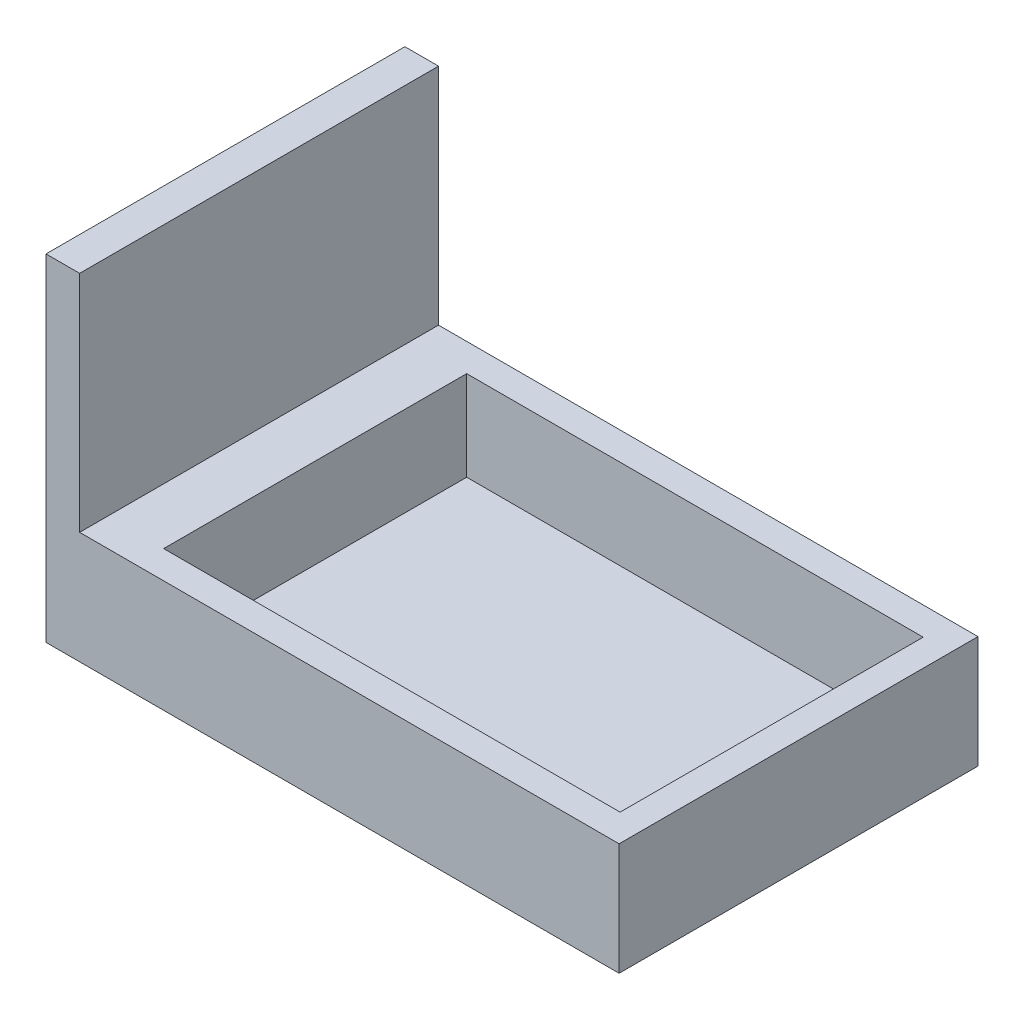
SolidWorks part; units mm, degrees
ref_plane "Front Plane" through (0, 0, 0) normal (0, 0, 1) x (1, 0, 0)
ref_plane "Top Plane" through (0, 0, 0) normal (0, 1, 0) x (1, 0, 0)
ref_plane "Right Plane" through (0, 0, 0) normal (1, 0, 0) x (0, 0, -1)
sketch "Sketch1" plane through (0, 0, 0) normal (0, 1, 0) x (1, 0, 0)
  line L0 (0, 0) -> (45.5, 0)
  line L1 (45.5, 0) -> (45.5, 32)
  line L2 (45.5, 32) -> (0, 32)
  line L3 (0, 32) -> (0, 0)
  dimension "D1" = 45.5
  dimension "D2" = 32
extrude "Boss-Extrude1" add sketch "Sketch1" along normal blind 10
sketch "Sketch2" plane through (0, 10, 0) normal (0, 1, 0) x (1, 0, 0)
  line L0 (1.5678, 0) -> (1.5678, 2.2044)
  line L1 (0, 0) -> (45.5, 0) construction
  line L2 (1.5678, 32) -> (1.5678, 21.3044) construction
  line L3 (45.5, 32) -> (0, 32) construction
  line L4 (0, 22.664) -> (2.5131, 22.664)
  line L5 (0, 32) -> (0, 0) construction
  line L6 (0, 2.4549) -> (2.4, 2.4549) construction
  line L7 (22.75, 29.51) -> (22.75, 2.49) construction
  line L8 (45.5131, 2.4549) -> (43.5131, 2.4549) construction
  line L9 (22.75, 32) -> (22.75, 0) construction
  line L11 (44.2924, 1.2457) -> (44.2924, 2.49)
  line L12 (2.4, 29.51) -> (2.4, 2.49)
  line L13 (2.4, 2.49) -> (43.1, 2.49)
  line L14 (43.1, 2.49) -> (43.1, 29.51)
  line L15 (43.1, 29.51) -> (2.4, 29.51)
  line L16 (0, 16) -> (45.5, 16) construction
  line L17 (45.5, 0) -> (45.5, 32) construction
  line L18 (0, 16) -> (45.5, 16) construction
  line L19 (2.4, 16) -> (43.1, 16)
  point P17 (23.0131, 2.695)
  point P31 (22.75, 16)
  dimension "D2" = 40.7
  dimension "D3" = 27.02
  dimension "D5" = 27.02
extrude "Cut-Extrude1" cut sketch "Sketch2" against normal blind 8
sketch "Sketch3" plane through (0, 0, 0) normal (-1, 0, 0) x (0, 0, 1)
  line L0 (-32, 10) -> (-32, 0)
  line L1 (-32, 0) -> (0, 0)
  line L2 (0, 0) -> (0, 10)
  line L3 (0, 10) -> (-32, 10)
extrude "Boss-Extrude2" add sketch "Sketch3" along normal blind 5.6
sketch "Sketch4" plane through (0, 10, 0) normal (0, 1, 0) x (1, 0, 0)
  line L0 (-5.6, 32) -> (-5.6, 0)
  line L1 (-5.6, 0) -> (-2.6, 0)
  line L2 (-5.6, 0) -> (45.5, 0) construction
  line L3 (-2.6, 0) -> (-2.6, 32)
  line L4 (45.5, 32) -> (-5.6, 32) construction
  line L5 (-2.6, 32) -> (-5.6, 32)
  dimension "D1" = 3
extrude "Boss-Extrude3" add sketch "Sketch4" along normal blind 20 contours L5 L0 L1 L3
